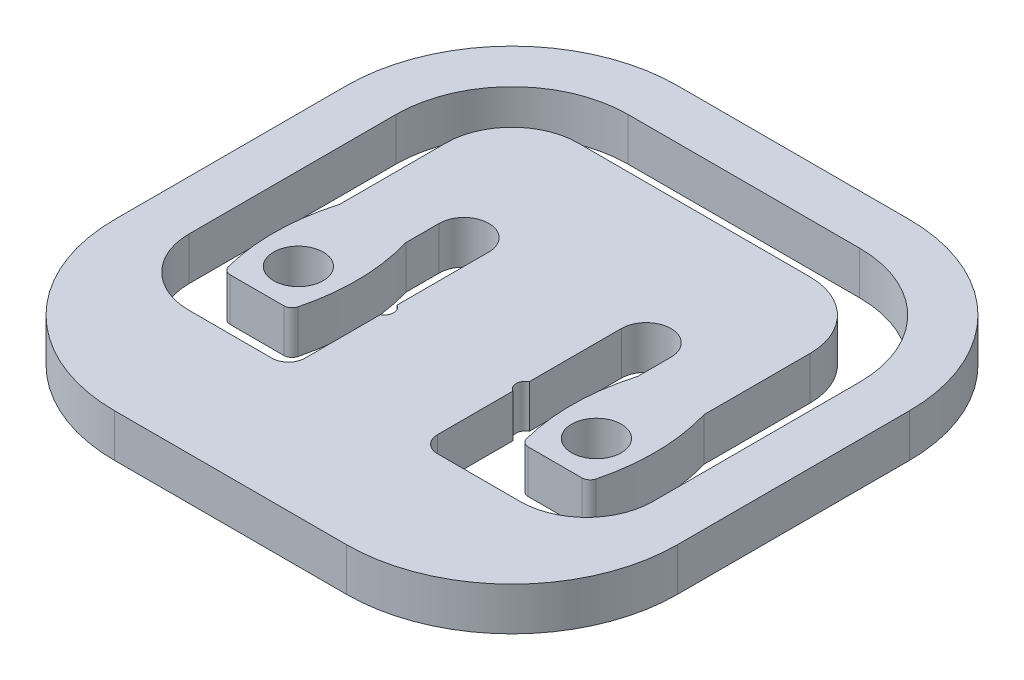
SolidWorks part; units mm, degrees
material "Plain Carbon Steel"
ref_plane "Front Plane" through (0, 0, 0) normal (0, 0, 1) x (1, 0, 0)
ref_plane "Top Plane" through (0, 0, 0) normal (0, 1, 0) x (1, 0, 0)
ref_plane "Right Plane" through (0, 0, 0) normal (1, 0, 0) x (0, 0, -1)
sketch "Sketch1" plane through (0, 0, 0) normal (0, 1, 0) x (1, 0, 0)
  line L1 (-17, 17) -> (17, 17)
  line L2 (-17, 17) -> (-17, -17)
  line L3 (-17, -17) -> (17, -17)
  line L4 (17, 17) -> (17, -17)
  line L5 (-17, 17) -> (17, -17) construction
  line L6 (-17, -17) -> (17, 17) construction
  point P0 (0, 0)
  dimension "D1" = 34
extrude "BASE" add sketch "Sketch1" along normal blind 2.6
fillet "BASE FILLET" radius 10 4 edges at (-17, 1.3, -17) (17, 1.3, -17) (17, 1.3, 17) (-17, 1.3, 17)
sketch "Sketch3" plane through (0, 2.6, 0) normal (0, 1, 0) x (1, 0, 0)
  line L0 (-14, 0.75) -> (-17, 0.75) construction
  line L1 (14, 0.75) -> (17, 0.75) construction
  line L3 (-10, -9.5) -> (10, -9.5)
  line L4 (-14, -5.5) -> (-14, 7)
  line L5 (-7, 14) -> (7, 14)
  line L6 (14, -5.5) -> (14, 7)
  line L7 (17, -7) -> (17, 7) construction
  line L9 (-17, 7) -> (-17, -7) construction
  line L10 (7, 17) -> (-7, 17) construction
  line L11 (-7, -17) -> (7, -17) construction
  line L12 (11.9497, 11.9497) -> (14.0711, 14.0711) construction
  arc A4 (-7, 14) -> (-14, 7) centre (-7, 7) ccw
  arc A5 (7, 14) -> (14, 7) centre (7, 7) cw
  arc A6 (-14, -5.5) -> (-10, -9.5) centre (-10, -5.5) ccw
  arc A7 (14, -5.5) -> (10, -9.5) centre (10, -5.5) cw
  arc A8 (17, 7) -> (7, 17) centre (7, 7) ccw construction
  dimension "D4" = 3
  dimension "D5" = 14
  dimension "D6" = 4
  dimension "D2" = 7
  dimension "D1" = 3
  dimension "D3" = 3
  dimension "D8" = 7.5
extrude "INNER CUT" cut sketch "Sketch3" against normal through all
sketch "Sketch4" plane through (0, 0, 0) normal (0, 1, 0) x (1, 0, 0)
  line L0 (-10, -9.5) -> (10, -9.5) construction
  line L2 (-4, 2.6) -> (-4, -9.5)
  line L5 (-7, 11) -> (0, 11)
  line L6 (-7, 2.6) -> (-7, 0.6)
  line L7 (-11, 7) -> (-11, 0.6)
  line L8 (-4, -9.5) -> (0, -9.5)
  line L9 (0, -9.5) -> (0, 11)
  line L10 (-7, 0.6) -> (-7, -6.4) construction
  line L11 (-7, -6.4) -> (-11, -6.4)
  line L12 (-7, 2.6) -> (-11, 2.6) construction
  line L13 (-9, 2.6) -> (-9, -6.4) construction
  line L14 (-6.5, -2.9) -> (-11.5, -2.9) construction
  line L15 (7, 14) -> (-7, 14) construction
  line L17 (-14, 7) -> (-14, -5.5) construction
  line L18 (-11.9497, 11.9497) -> (-9.8284, 9.8284) construction
  arc A0 (-4, 2.6) -> (-7, 2.6) centre (-5.5, 2.6) ccw
  arc A1 (-7, -6.4) -> (-7, 0.6) centre (-19, -2.9) ccw
  arc A2 (-11, -6.4) -> (-11, 0.6) centre (1, -2.9) cw
  arc A3 (-7, 11) -> (-11, 7) centre (-7, 7) ccw
  arc A5 (-7, 14) -> (-14, 7) centre (-7, 7) ccw construction
  point P6 (0, -9.5)
  dimension "D1" = 3
  dimension "D10" = 3
  dimension "D2" = 5
  dimension "D3" = 4
  dimension "D4" = 3
  dimension "D5" = 2
  dimension "D6" = 4
  dimension "D7" = 7
  dimension "D8" = 17.4
  dimension "D9" = 3
extrude "INNER LEFT PROFILE" add sketch "Sketch4" along normal up to surface (2.6 mm away) up to face at (0, 2.6, -1.6553)
sketch "Sketch5" plane through (0, 2.6, 0) normal (0, 1, 0) x (1, 0, 0)
  line L0 (-9, -6.4) -> (-9, -3.9) construction
  line L1 (-11, -6.4) -> (-7, -6.4) construction
  circle A0 centre (-9, -3.9) radius 1.5
  dimension "D2" = 3
  dimension "D1" = 2.5
extrude "RIVET HOLE" cut sketch "Sketch5" against normal through all
sketch "Sketch6" plane through (0, 2.6, 0) normal (0, 1, 0) x (1, 0, 0)
  line L0 (-4, -2.95) -> (-4, -3.95)
  line L1 (-4, 2.6) -> (-4, -9.5) construction
  line L2 (-3.7, -3.45) -> (-4, -3.45) construction
  arc A0 (-4, -3.95) -> (-4, -2.95) centre (-4.2667, -3.45) ccw
  dimension "D1" = 0.3
  dimension "D2" = 1
extrude "GROOVED PARTIAL CIRCLE CUT" cut sketch "Sketch6" against normal through all
fillet "ILP F" radius 0.5 2 edges at (-11, 1.3, 6.4) (-7, 1.3, 6.4)
fillet "IC F" radius 1 1 edges at (-4, 1.3, 9.5)
mirror "MIRROR INNER FEATURES" about plane through (0, 0, 0) normal (1, 0, 0) of "IC F", "RIVET HOLE", "INNER LEFT PROFILE", "ILP F", "GROOVED PARTIAL CIRCLE CUT"
